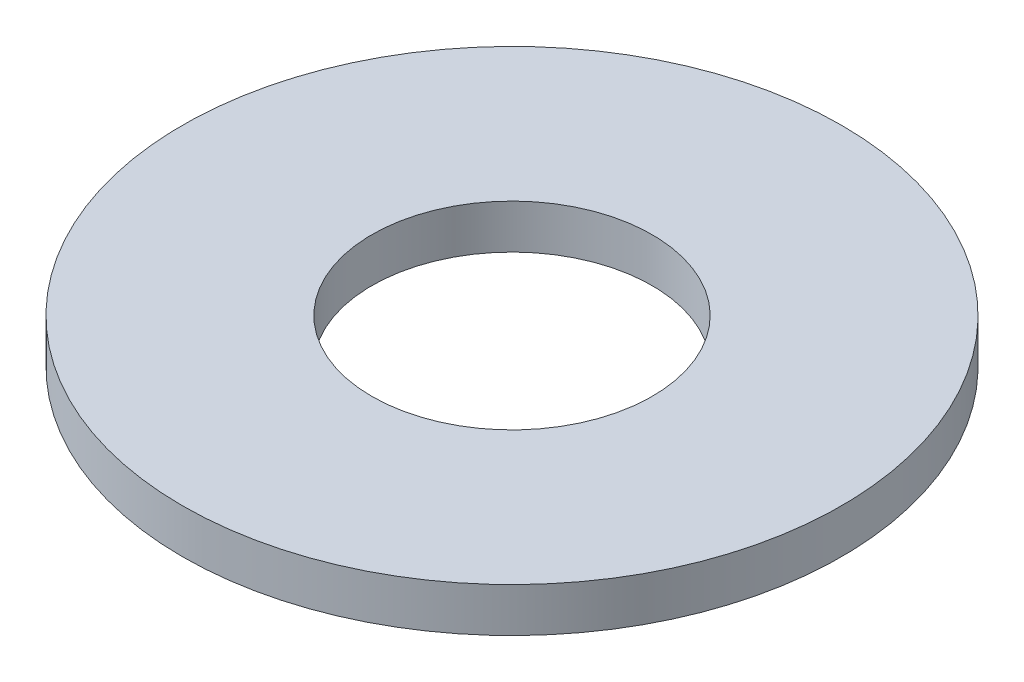
SolidWorks part; units mm, degrees
ref_plane "Front Plane" through (0, 0, 0) normal (0, 0, 1) x (1, 0, 0)
ref_plane "Top Plane" through (0, 0, 0) normal (0, 1, 0) x (1, 0, 0)
ref_plane "Right Plane" through (0, 0, 0) normal (1, 0, 0) x (0, 0, -1)
sketch "Sketch1" plane through (0, 0, 0) normal (0, 1, 0) x (1, 0, 0)
  circle A0 centre (0, 0) radius 1.94
  circle A1 centre (0, 0) radius 0.825
  dimension "D1" = 3.88
  dimension "D2" = 1.65
extrude "Boss-Extrude1" add sketch "Sketch1" along normal blind 0.26
